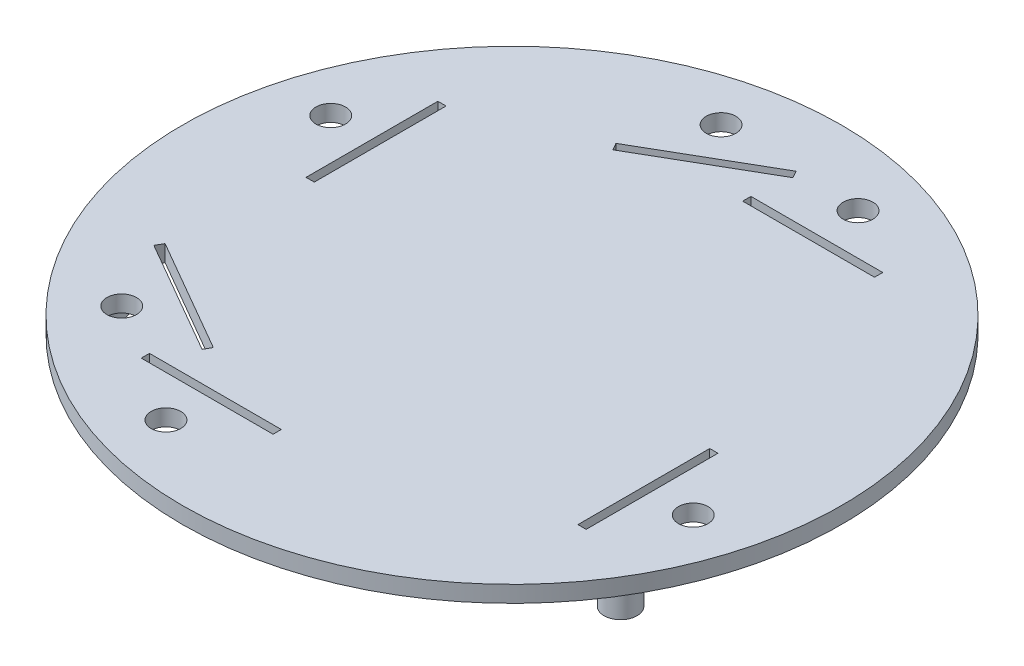
SolidWorks part; units mm, degrees
ref_plane "Front Plane" through (0, 0, 0) normal (0, 0, 1) x (1, 0, 0)
ref_plane "Top Plane" through (0, 0, 0) normal (0, 1, 0) x (1, 0, 0)
ref_plane "Right Plane" through (0, 0, 0) normal (1, 0, 0) x (0, 0, -1)
sketch "Sketch1" plane through (0, 0, 0) normal (0, 1, 0) x (1, 0, 0)
  circle A1 centre (0, 0) radius 127
  dimension "D1" = 254
extrude "Boss-Extrude1" add sketch "Sketch1" along normal blind 6.35
sketch "Sketch2" plane through (0, 0, 0) normal (0, -1, 0) x (1, 0, 0)
  circle A0 centre (0, -114.3) radius 6.35
  circle A1 centre (-98.9867, 57.15) radius 6.35
  circle A2 centre (98.9867, 57.15) radius 6.35
  point P2 (-58.176, 55.0673)
  point P4 (0, 0)
  point P10 (0, 0)
  dimension "D1" = 12.7
  dimension "D2" = 114.3
  dimension "D3" = 3
extrude "Boss-Extrude2" add sketch "Sketch2" along normal blind 12.7
sketch "Sketch3" plane through (0, 6.35, 0) normal (0, 1, 0) x (1, 0, 0)
  line L0 (-6.35, -85.725) -> (-57.15, -85.725)
  line L1 (82.55, -6.35) -> (85.725, -6.35)
  line L2 (82.55, -6.35) -> (82.55, -57.15)
  line L3 (82.55, -57.15) -> (85.725, -57.15)
  line L4 (85.725, -6.35) -> (85.725, -57.15)
  line L5 (-6.35, -82.55) -> (-57.15, -82.55)
  line L6 (-6.35, -82.55) -> (-6.35, -85.725)
  line L7 (-57.15, -82.55) -> (-57.15, -85.725)
  line L8 (-85.725, 6.35) -> (-85.725, 57.15)
  line L9 (-82.55, 6.35) -> (-82.55, 57.15)
  line L10 (-82.55, 6.35) -> (-85.725, 6.35)
  line L11 (-82.55, 57.15) -> (-85.725, 57.15)
  line L12 (6.35, 85.725) -> (57.15, 85.725)
  line L13 (6.35, 82.55) -> (57.15, 82.55)
  line L14 (6.35, 82.55) -> (6.35, 85.725)
  line L15 (57.15, 82.55) -> (57.15, 85.725)
  line L16 (-48.3618, -71.065) -> (-92.3559, -45.665)
  line L17 (-46.7743, -68.3154) -> (-90.7684, -42.9154)
  line L18 (-46.7743, -68.3154) -> (-48.3618, -71.065)
  line L19 (-90.7684, -42.9154) -> (-92.3559, -45.665)
  line L20 (-37.3632, 77.415) -> (6.6309, 102.815)
  line L21 (-35.7757, 74.6654) -> (8.2184, 100.0654)
  line L22 (-35.7757, 74.6654) -> (-37.3632, 77.415)
  line L23 (8.2184, 100.0654) -> (6.6309, 102.815)
  circle A0 centre (101.6, -31.75) radius 5.715
  circle A1 centre (-31.75, -101.6) radius 5.715
  circle A2 centre (-101.6, 31.75) radius 5.715
  circle A3 centre (31.75, 101.6) radius 5.715
  circle A4 centre (-78.2963, -72.1132) radius 5.715
  circle A5 centre (-23.3037, 103.8632) radius 5.715
  point P19 (0, 0)
  point P28 (0, 0)
  point P31 (-87.532, -88.407)
  point P38 (0, 0)
  point P39 (0, 0)
  point P42 (0, 0)
  dimension "D7" = 19.05
  dimension "D8" = 11.43
  dimension "D1" = 3.175
  dimension "D2" = 82.55
  dimension "D3" = 50.8
  dimension "D4" = 6.35
  dimension "D9" = 25.4
  dimension "D5" = 4
  dimension "D6" = 3
  dimension "D10" = 4
  dimension "D11" = 3
extrude "Cut-Extrude1" cut sketch "Sketch3" against normal through all
